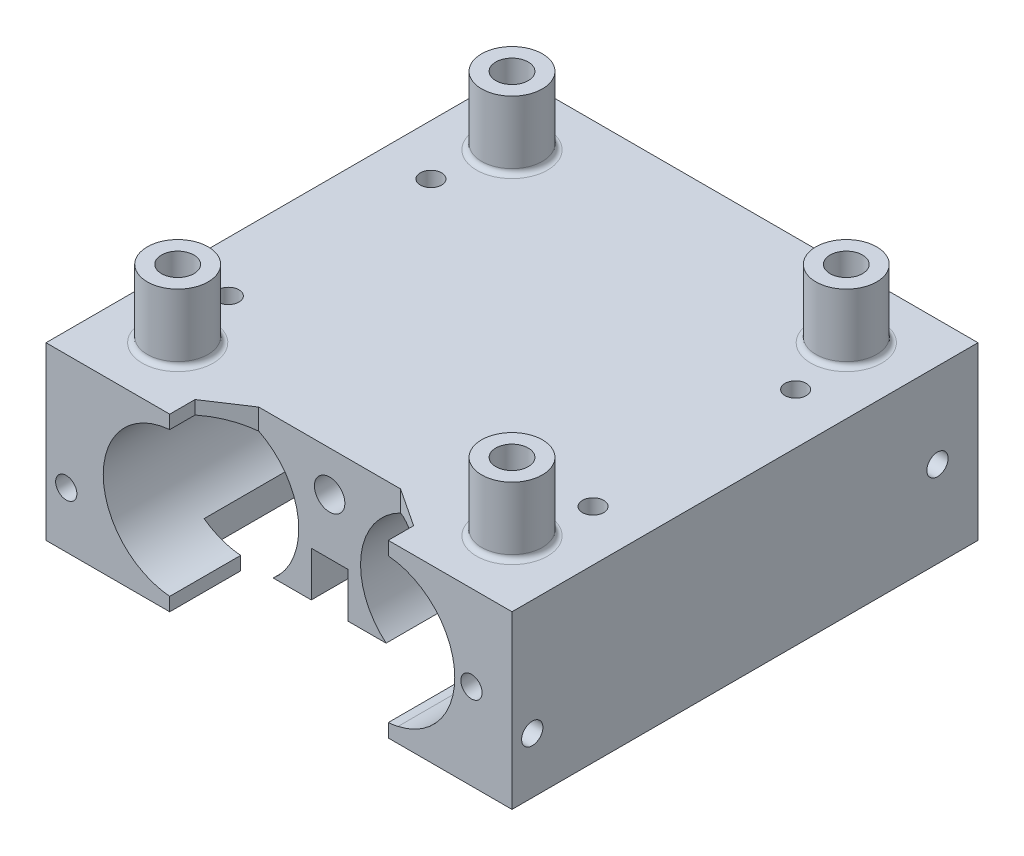
SolidWorks part; units mm, degrees
material "PTFE (general)"
ref_plane "Alzado" through (0, 0, 0) normal (0, 0, 1) x (1, 0, 0)
ref_plane "Planta" through (0, 0, 0) normal (0, 1, 0) x (1, 0, 0)
ref_plane "Vista lateral" through (0, 0, 0) normal (1, 0, 0) x (0, 0, -1)
sketch "Croquis4" plane through (0, 0, 0) normal (0, 1, 0) x (1, 0, 0)
  line L1 (-23, 23) -> (23, 23)
  line L2 (-23, 23) -> (-23, -23)
  line L3 (-23, -23) -> (23, -23)
  line L4 (23, 23) -> (23, -23)
  line L5 (-23, 23) -> (23, -23) construction
  line L6 (-23, -23) -> (23, 23) construction
  point P0 (0, 0)
  dimension "D1" = 46
  dimension "D2" = 46
extrude "Saliente-Extruir1" add sketch "Croquis4" along normal blind 16.9 contours L2 L3 L4 L1
hole_wizard "Taladro1" positions "Croquis7" profile "Croquis9" legacy
sketch "Croquis7" plane through (0, 0, 23) normal (0, 0, 1) x (1, 0, 0)
  point P0 (-21, 5.5)
  point P2 (19, 8.5)
  dimension "D1" = 2
  dimension "D2" = 5.5
  dimension "D3" = 4
  dimension "D4" = 8.5
sketch "Croquis9" plane through (-21, 5.5, 23) normal (1, 0, 0) x (0, -1, 0)
  line L0 (0, 0) -> (0, 3.6309)
  line L1 (0, 3.6309) -> (1.05, 3)
  line L2 (1.05, 3) -> (1.05, 0)
  line L4 (1.05, 0) -> (0, 0)
  line L6 (0, 3.6309) -> (-1.05, 3) construction
  line L7 (0, -4.2442) -> (0, 117.3081) construction
  dimension "Diámetro" = 2.1
  dimension "Profundidad" = 3
  dimension "Ángulo de perforado" = 118
hole_wizard "Taladro6" positions "Croquis21" profile "Croquis20" legacy
sketch "Croquis21" plane through (23, 0, 0) normal (1, 0, 0) x (0, 0, -1)
  point P0 (-21, 5.5)
  point P1 (19, 8.5)
  dimension "D1" = 2
  dimension "D2" = 5.5
  dimension "D3" = 4
  dimension "D4" = 8.5
sketch "Croquis20" plane through (23, 5.5, 21) normal (0, 1, 0) x (0, 0, -1)
  line L0 (0, 0) -> (0, 3.6309)
  line L1 (0, 3.6309) -> (1.05, 3)
  line L2 (1.05, 3) -> (1.05, 0)
  line L4 (1.05, 0) -> (0, 0)
  line L6 (0, 3.6309) -> (-1.05, 3) construction
  line L7 (0, -4.2442) -> (0, 117.3081) construction
  dimension "Diámetro" = 2.1
  dimension "Profundidad" = 3
  dimension "Ángulo de perforado" = 118
hole_wizard "Taladro7" positions "Croquis22" profile "Croquis23" legacy
sketch "Croquis22" plane through (0, 0, -23) normal (0, 0, -1) x (-1, 0, 0)
  line L1 (23, 0) -> (-23, 0) construction
  point P0 (-21, 5.5)
  point P2 (19, 8.5)
  dimension "D1" = 4
  dimension "D2" = 8.5
  dimension "D3" = 5.5
  dimension "D4" = 2
sketch "Croquis23" plane through (21, 5.5, -23) normal (1, 0, 0) x (0, 1, 0)
  line L0 (0, 0) -> (0, 3.6309)
  line L1 (0, 3.6309) -> (1.05, 3)
  line L2 (1.05, 3) -> (1.05, 0)
  line L4 (1.05, 0) -> (0, 0)
  line L6 (0, 3.6309) -> (-1.05, 3) construction
  line L7 (0, -4.2442) -> (0, 117.3081) construction
  dimension "Diámetro" = 2.1
  dimension "Profundidad" = 3
  dimension "Ángulo de perforado" = 118
hole_wizard "Taladro8" positions "Croquis24" profile "Croquis26" legacy
sketch "Croquis24" plane through (-23, 0, 0) normal (-1, 0, 0) x (0, 0, 1)
  line L0 (23, 16.9) -> (23, 0) construction
  line L2 (-23, 0) -> (23, 0) construction
  point P0 (-21, 5.5)
  point P2 (19, 8.5)
  dimension "D1" = 8.5
  dimension "D2" = 4
  dimension "D3" = 2
  dimension "D4" = 5.5
sketch "Croquis26" plane through (-23, 5.5, -21) normal (0, 1, 0) x (0, 0, 1)
  line L0 (0, 0) -> (0, 3.6309)
  line L1 (0, 3.6309) -> (1.05, 3)
  line L2 (1.05, 3) -> (1.05, 0)
  line L4 (1.05, 0) -> (0, 0)
  line L6 (0, 3.6309) -> (-1.05, 3) construction
  line L7 (0, -4.2442) -> (0, 117.3081) construction
  dimension "Diámetro" = 2.1
  dimension "Profundidad" = 3
  dimension "Ángulo de perforado" = 118
sketch "Croquis28" plane through (0, 0, 0) normal (0, -1, 0) x (1, 0, 0)
  line L0 (0, 28.2153) -> (0, -35.2577) construction
  line L1 (34.8862, 0) -> (-35.5377, 0) construction
  line L2 (-23, -23) -> (-23, 23) construction
  line L4 (-23, 23) -> (23, 23) construction
  point P5 (-21, 7)
  point P12 (21, 7)
  point P15 (21, -7)
  point P16 (-21, -7)
  dimension "D1" = 2
  dimension "D2" = 16
hole_wizard "Taladro10" positions "Croquis3D2" profile "Croquis30" legacy
sketch3d "Croquis3D2"
  point P0 (-21, 0, 7)
  point P3 (21, 0, 7)
  point P6 (21, 0, -7)
  point P9 (-21, 0, -7)
sketch "Croquis30" plane through (-21, 0, 7) normal (1, 0, 0) x (0, 0, -1)
  line L0 (0, 0) -> (0, 3.6309)
  line L1 (0, 3.6309) -> (1.05, 3)
  line L2 (1.05, 3) -> (1.05, 0)
  line L4 (1.05, 0) -> (0, 0)
  line L6 (0, 3.6309) -> (-1.05, 3) construction
  line L7 (0, -4.2442) -> (0, 117.3081) construction
  dimension "Diámetro" = 2.1
  dimension "Profundidad" = 3
  dimension "Ángulo de perforado" = 118
sketch "Croquis34" plane through (0, 16.9, 0) normal (0, 1, 0) x (1, 0, 0)
  line L0 (0, 23) -> (0, -23) construction
  line L1 (-23, 23) -> (23, 23) construction
  line L2 (-23, -23) -> (23, -23) construction
  line L3 (0, -23) -> (0, 0) construction
  line L4 (0, 0) -> (23, 0) construction
  line L5 (23, 23) -> (23, -23) construction
  line L6 (23, 0) -> (-23, 0) construction
  line L7 (-23, 23) -> (-23, -23) construction
  point P6 (-18, 10)
  point P15 (18, 10)
  point P17 (18, -10)
  point P19 (-18, -10)
  dimension "D1" = 13
  dimension "D2" = 5
hole_wizard "Taladro11" positions "Croquis3D4" profile "Croquis35" legacy
sketch3d "Croquis3D4"
  point P0 (-18, 16.9, -10)
  point P3 (18, 16.9, -10)
  point P6 (18, 16.9, 10)
  point P9 (-18, 16.9, 10)
sketch "Croquis35" plane through (-18, 16.9, -10) normal (1, 0, 0) x (0, 0, 1)
  line L0 (0, 0) -> (0, 3.6309)
  line L1 (0, 3.6309) -> (1.05, 3)
  line L2 (1.05, 3) -> (1.05, 0)
  line L4 (1.05, 0) -> (0, 0)
  line L6 (0, 3.6309) -> (-1.05, 3) construction
  line L7 (0, -4.2442) -> (0, 117.3081) construction
  dimension "Diámetro" = 2.1
  dimension "Profundidad" = 3
  dimension "Ángulo de perforado" = 118
sketch "Croquis36" plane through (0, 16.9, 0) normal (0, 1, 0) x (1, 0, 0)
  line L0 (-23, 23) -> (23, 23) construction
  line L2 (-23, 23) -> (-23, -23) construction
  line L3 (0, 23) -> (0, -23) construction
  line L4 (-23, -23) -> (23, -23) construction
  line L5 (0, -23) -> (0, 0) construction
  line L6 (0, 0) -> (23, 0) construction
  line L7 (23, 23) -> (23, -23) construction
  line L8 (23, 0) -> (-23, 0) construction
  circle A0 centre (-16.5, 16.5) radius 3
  circle A1 centre (16.5, 16.5) radius 3
  circle A2 centre (16.5, -16.5) radius 3
  circle A3 centre (-16.5, -16.5) radius 3
  dimension "D1" = 6.5
  dimension "D3" = 6
  dimension "D2" = 6.5
extrude "Saliente-Extruir3" add sketch "Croquis36" along normal blind 6.7
hole_wizard "Taladro12" positions "Croquis3D5" profile "Croquis37" legacy
sketch3d "Croquis3D5"
  line L0 (-16.5, 23.6, 16.5) -> (-16.5, 16.9, 16.5) construction
  line L1 (16.5, 23.6, 16.5) -> (16.5, 16.9, 16.5) construction
  line L2 (16.5, 23.6, -16.5) -> (16.5, 16.9, -16.5) construction
  line L3 (-16.5, 23.6, -16.5) -> (-16.5, 16.9, -16.5) construction
  point P25 (-16.5, 23.6, 16.5)
  point P29 (16.5, 23.6, 16.5)
  point P33 (16.5, 23.6, -16.5)
  point P37 (-16.5, 23.6, -16.5)
sketch "Croquis37" plane through (-16.5, 23.6, 16.5) normal (1, 0, 0) x (0, 0, 1)
  line L0 (0, 0) -> (0, 8.5614)
  line L1 (0, 8.5614) -> (1.6, 7.6)
  line L2 (1.6, 7.6) -> (1.6, 0)
  line L4 (1.6, 0) -> (0, 0)
  line L6 (0, 8.5614) -> (-1.6, 7.6) construction
  line L7 (0, -4.2442) -> (0, 117.3081) construction
  dimension "Diámetro" = 3.2
  dimension "Profundidad" = 7.6
  dimension "Ángulo de perforado" = 118
fillet "Redondeo1" radius 0.5 4 edges at (16.5, 16.9, 13.5) (16.5, 16.9, -19.5) (-16.5, 16.9, -19.5) (-16.5, 16.9, 13.5)
sketch "Croquis32" plane through (0, 0, 23) normal (0, 0, 1) x (1, 0, 0)
  line L0 (0, 16.9) -> (0, 0) construction
  line L1 (-23, 16.9) -> (23, 16.9) construction
  line L2 (23, 8.45) -> (-23, 8.45) construction
  line L3 (23, 16.9) -> (23, 0) construction
  line L4 (-23, 16.9) -> (-23, 0) construction
  circle A0 centre (-10.2, 8.45) radius 7.15
  circle A1 centre (10.2, 8.45) radius 7.15
  dimension "D1" = 14.3
  dimension "D2" = 12.8
  dimension "D3" = 0
extrude "Cortar-Extruir1" cut sketch "Croquis32" against normal up to surface (46 mm away) up to face at (19.95, 5.5, -23)
ref_plane "Plano1" through (0, 0, 21) normal (0, 0, 1) x (1, 0, 0)
sketch "Croquis42" plane through (0, 0, 0) normal (0, -1, 0) x (1, 0, 0)
  line L0 (-11.7467, 16) -> (-11.7467, -16)
  line L1 (-11.7467, -16) -> (11.7467, -16)
  line L2 (0, -18.5488) -> (0, 30.48) construction
  line L3 (-11.7467, 16) -> (11.7467, 16)
  line L4 (-23, 23) -> (23, 23) construction
  line L5 (-23, -23) -> (23, -23) construction
  line L6 (11.7467, 16) -> (11.7467, -16)
  point P12 (0, 16)
  point P13 (0, -16)
  dimension "D1" = 7
  dimension "D2" = 7
extrude "Cortar-Extruir5" cut sketch "Croquis42" against normal blind 3
sketch "Croquis39" plane through (0, 16.9, 0) normal (0, 1, 0) x (1, 0, 0)
  line L0 (0, 0) -> (0, -23) construction
  line L1 (-23, -23) -> (23, -23) construction
  line L2 (-10.7871, -20.5) -> (-10.7871, -23)
  line L3 (-10.7871, -23) -> (-10.7871, -18) construction
  line L4 (-10.7871, -18) -> (0, -18) construction
  line L5 (-10.7871, -20.5) -> (-7, -18)
  line L6 (-10.7871, -23) -> (10.7871, -23)
  line L8 (7, -18) -> (-7, -18)
  line L9 (10.7871, -20.5) -> (7, -18)
  line L10 (10.7871, -20.5) -> (10.7871, -23)
  line L11 (7, -18) -> (13.8091, -22.4949) construction
  line L12 (23, -22.4949) -> (-23, -22.4949) construction
  line L13 (23, 23) -> (23, -23) construction
  line L14 (-23, 23) -> (-23, -23) construction
  dimension "D1" = 5
  dimension "D2" = 4.4949
  dimension "D3" = 7
  dimension "D4" = 8.1589
extrude "Cortar-Extruir3" cut sketch "Croquis39" against normal through all
sketch "Croquis43" plane through (0, 0, -16) normal (0, 0, 1) x (1, 0, 0)
  line L0 (-11.7467, 0) -> (-14.3967, 0)
  line L1 (-14.3967, 0) -> (-14.3967, 3.3936)
  line L2 (-14.3967, 3.3936) -> (-11.7467, 3.3936)
  line L3 (-11.7467, 3.3936) -> (-11.7467, 0)
  dimension "D1" = 2.65
extrude "Cortar-Extruir6" cut sketch "Croquis43" along normal up to surface (32 mm away) up to face at (0, 1.2482, 16)
sketch "Croquis44" plane through (0, 0, -23) normal (0, 0, -1) x (-1, 0, 0)
  line L0 (-10.2, 8.45) -> (10.2, 8.45) construction
  line L1 (-3.9771, 9.4087) -> (-3.9771, 7.4913)
  line L2 (-3.9771, 9.4087) -> (-2.725, 9.4087) construction
  line L3 (0, 0) -> (0, 19.3675) construction
  line L4 (-3.9771, 7.4913) -> (-0.9755, 7.4913)
  line L5 (3.9771, 9.4087) -> (3.9771, 7.4913)
  line L6 (-0.9755, 7.4913) -> (-0.9755, 0)
  line L7 (23, 0) -> (-23, 0) construction
  line L8 (0.9755, 7.4913) -> (0.9755, 0)
  line L9 (0.9755, 0) -> (-0.9755, 0)
  line L10 (0.9755, 7.4913) -> (3.9771, 7.4913)
  line L11 (-2.725, 9.4087) -> (-2.725, 12.4839) construction
  line L12 (-2.725, 12.4839) -> (2.725, 12.4839)
  line L13 (2.725, 9.4087) -> (2.725, 12.4839) construction
  line L14 (2.725, 9.4087) -> (3.9771, 9.4087) construction
  line L15 (-2.725, 12.4839) -> (-4.8787, 12.4839)
  line L16 (-4.8787, 12.4839) -> (-4.8787, 9.4087)
  line L17 (-4.8787, 9.4087) -> (-3.9771, 9.4087)
  line L18 (4.8787, 9.4087) -> (3.9771, 9.4087)
  line L19 (2.725, 12.4839) -> (4.8787, 12.4839)
  line L20 (4.8787, 12.4839) -> (4.8787, 9.4087)
  circle A0 centre (10.2, 8.45) radius 7.15 construction
  circle A1 centre (-10.2, 8.45) radius 7.15 construction
  circle A2 centre (10.2, 8.45) radius 7.15 construction
  circle A3 centre (-10.2, 8.45) radius 7.15 construction
  point P13 (-3.9771, 8.45)
  point P15 (0, 7.4913)
  point P16 (0, 9.4087)
  point P28 (0, 12.4839)
  dimension "D1" = 5.45
extrude "Cortar-Extruir7" cut sketch "Croquis44" against normal blind 4
sketch "Croquis45" plane through (0, 0, -19) normal (0, 0, -1) x (-1, 0, 0)
  line L0 (-0.9755, 0) -> (0.9755, 0)
  line L1 (0.9755, 0) -> (0.9755, 3)
  line L2 (0.9755, 0) -> (0.9755, 7.4913) construction
  line L3 (0.9755, 3) -> (-0.9755, 3)
  line L4 (-0.9755, 7.4913) -> (-0.9755, 0) construction
  line L5 (-0.9755, 3) -> (-0.9755, 0)
  line L7 (5.5718, 3) -> (-5.5718, 3) construction
extrude "Cortar-Extruir8" cut sketch "Croquis45" against normal up to next
sketch "Croquis46" plane through (0, 0, 18) normal (0, 0, 1) x (1, 0, 0)
  line L0 (0, 0) -> (-1.8143, 0)
  line L1 (7, 0) -> (-7, 0) construction
  line L2 (-1.8143, 2.4987) -> (-1.8143, 7.4277)
  line L3 (-1.8143, 7.4277) -> (0, 7.4277)
  line L4 (0, 0) -> (0, 7.4277) construction
  line L5 (1.8143, 2.4987) -> (1.8143, 7.4277)
  line L6 (1.8143, 7.4277) -> (0, 7.4277)
  line L7 (1.8143, 0) -> (0, 0)
  line L8 (3.1313, 0) -> (1.8143, 2.4987)
  line L9 (3.1313, 0) -> (1.8143, 0)
  line L10 (-3.1313, 0) -> (-1.8143, 2.4987)
  line L11 (-3.1313, 0) -> (-1.8143, 0)
extrude "Cortar-Extruir9" cut sketch "Croquis46" against normal blind 31
sketch "Croquis47" plane through (0, 0, 18) normal (0, 0, 1) x (1, 0, 0)
  line L0 (-7, 0) -> (-7, 3)
  line L1 (-7, 3) -> (7.0062, 3)
  line L2 (7.0062, 3) -> (7, 0)
  line L3 (7, 0) -> (-7, 0)
  line L4 (-5.5718, 3) -> (-0.9755, 3) construction
extrude "Cortar-Extruir10" cut sketch "Croquis47" against normal up to next
sketch "Croquis49" plane through (0, 0, 0) normal (0, 0, 1) x (1, 0, 0)
  line L0 (10.7871, 0) -> (10.7871, 2.27)
  line L1 (10.7871, 2.27) -> (7, 2.27)
  line L2 (7, 2.27) -> (7, 0)
  line L4 (7, 0) -> (10.7871, 0)
  line L5 (7, 0) -> (7, 2.0561) construction
  line L6 (0, 0) -> (0, 5.694) construction
  line L7 (-7, 0) -> (-10.7871, 0)
  line L8 (-10.7871, 0) -> (-10.7871, 2.27)
  line L9 (-10.7871, 2.27) -> (-7, 2.27)
  line L10 (-7, 2.27) -> (-7, 0)
extrude "Cortar-Extruir11" cut sketch "Croquis49" along normal up to surface (23 mm away) up to face at (-15.9519, 8.45, 23)
sketch "Croquis53" plane through (0, 0, 18) normal (0, 0, 1) x (1, 0, 0)
  line L1 (7, 16.9) -> (-7, 16.9) construction
  circle A0 centre (0, 12.9154) radius 1.5
  circle A1 centre (0, 12.9154) radius 3.9846 construction
  arc A2 (-5.5718, 3) -> (-7, 14.8439) centre (-10.2, 8.45) ccw construction
  arc A6 (7, 14.8439) -> (5.5718, 3) centre (10.2, 8.45) ccw construction
  point P8 (-3.5776, 11.1611)
  point P9 (3.3144, 10.7037)
  dimension "D1" = 3
extrude "Cortar-Extruir13" cut sketch "Croquis53" against normal through all
